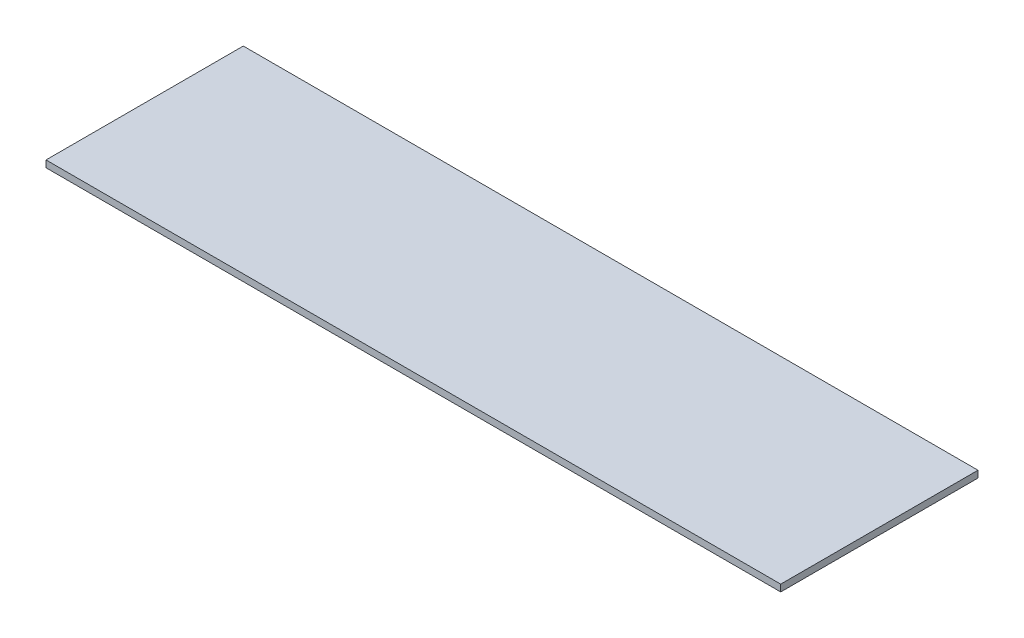
SolidWorks part; units mm, degrees
ref_plane "Front Plane" through (0, 0, 0) normal (0, 0, 1) x (1, 0, 0)
ref_plane "Top Plane" through (0, 0, 0) normal (0, 1, 0) x (1, 0, 0)
ref_plane "Right Plane" through (0, 0, 0) normal (1, 0, 0) x (0, 0, -1)
sketch "Sketch1" plane through (0, 0, 0) normal (0, 1, 0) x (1, 0, 0)
  line L1 (0, 0) -> (-540, 0)
  line L2 (0, 0) -> (0, -145)
  line L3 (0, -145) -> (-540, -145)
  line L4 (-540, 0) -> (-540, -145)
  dimension "D1" = 540
  dimension "D2" = 145
extrude "Boss-Extrude1" add sketch "Sketch1" along normal blind 5
